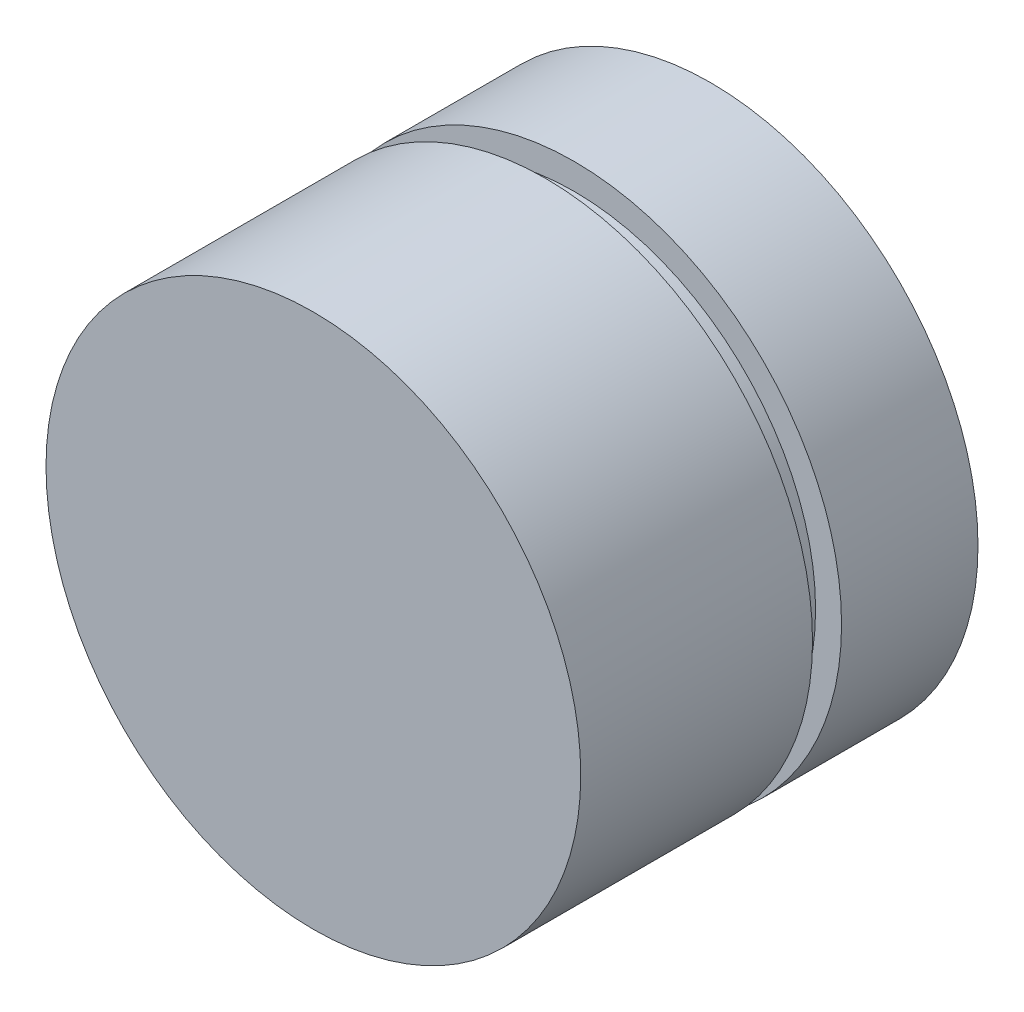
SolidWorks part; units mm, degrees
ref_plane "Alzado" through (0, 0, 0) normal (0, 0, 1) x (1, 0, 0)
ref_plane "Planta" through (0, 0, 0) normal (0, 1, 0) x (1, 0, 0)
ref_plane "Vista lateral" through (0, 0, 0) normal (1, 0, 0) x (0, 0, -1)
sketch "Croquis6" plane through (0, 0, 0) normal (0, 1, 0) x (1, 0, 0)
  line L0 (0, 0) -> (0, 32.5747) construction
  line L1 (17.5, 15.1698) -> (15.8, 15.1698)
  line L2 (17.5, 0) -> (17.5, 15.1698)
  line L3 (15.8, 15.1698) -> (15.8, 17.0698)
  line L4 (15.8, 17.0698) -> (17.5, 17.0698)
  line L5 (17.5, 17.0698) -> (17.5, 26)
  line L6 (17.5, 26) -> (0, 26)
  line L7 (0, 26) -> (0, 0)
  line L8 (0, 0) -> (17.5, 0)
  dimension "D1" = 35
  dimension "D2" = 1.7
  dimension "D3" = 1.9
  dimension "D4" = 26
revolve "Revolución1" add sketch "Croquis6" angle 360 about L0
sketch "Croquis7" plane through (0, 0, 0) normal (0, 1, 0) x (1, 0, 0)
  line L0 (0, 0) -> (0, 26.0133) construction
  line L1 (0, 26) -> (0, 17.0698) construction
  line L2 (0, 26.0133) -> (15.6, 26.0133)
  line L5 (0, 26.0133) -> (0, 11.1133)
  line L8 (15.6, 26.0133) -> (15.6, 17.2133)
  line L10 (13.88, 11.1067) -> (0, 11.1133)
  line L11 (13.88, 11.1067) -> (15.6, 17.2133)
  point P7 (15.6, 7.2133)
  dimension "D1" = 15.6
  dimension "D2" = 27.76
  dimension "D3" = 14.9
  dimension "D4" = 15.73
  dimension "D5" = 8.8
revolve "Cortar-Revolución1" cut sketch "Croquis7" angle 360 about L0
sketch "Croquis8" plane through (0, 0, 0) normal (0, 1, 0) x (1, 0, 0)
  line L0 (0, 0) -> (0, 30.814) construction
  line L1 (0, 17.2133) -> (0, 11.1133)
  line L2 (-15.6, 17.2133) -> (15.6, 17.2133)
  line L3 (0, 17.2133) -> (5, 17.2133)
  line L4 (0, 11.1133) -> (5, 11.1133)
  line L6 (5, 11.1133) -> (5, 17.2133)
  line L7 (5, 17.2133) -> (0, 17.2133)
  dimension "D2" = 6.1
  dimension "D3" = 5
  dimension "D1" = 0
revolve "Revolución4" add sketch "Croquis8" angle 360 about L0
